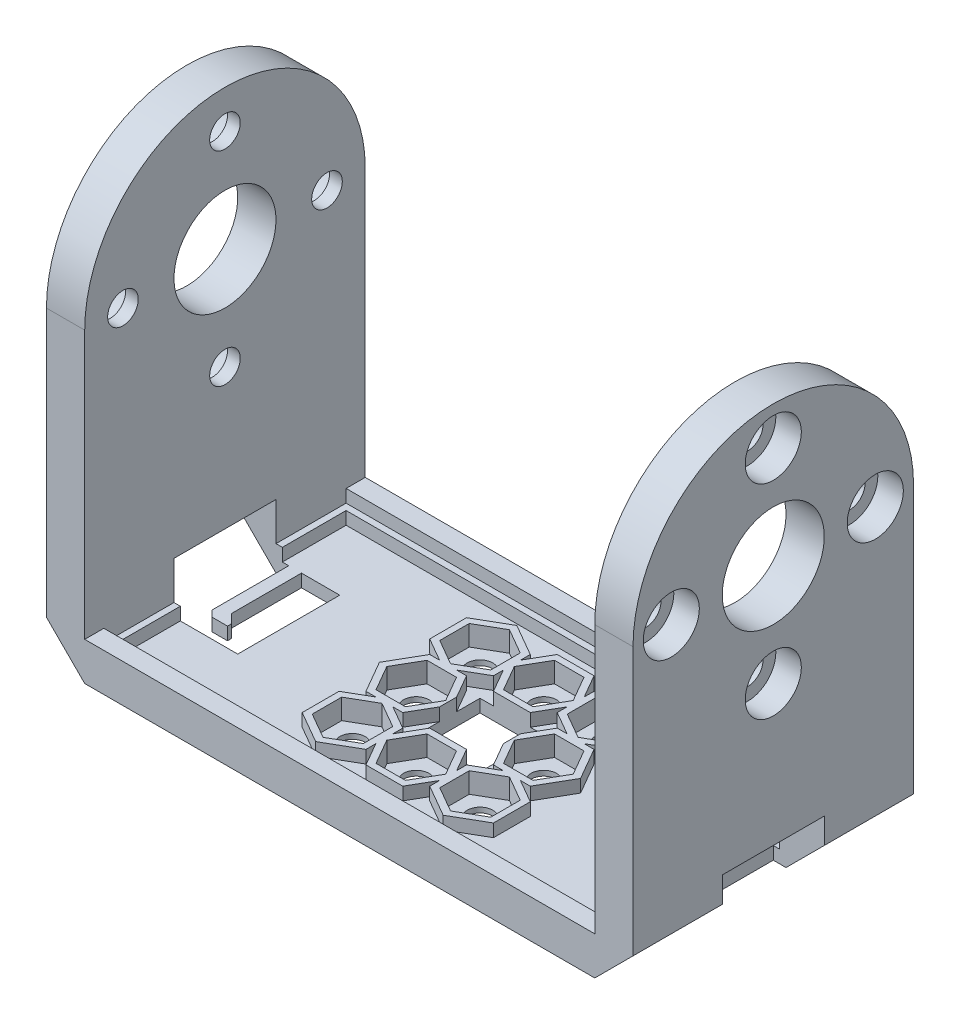
SolidWorks part; units mm, degrees
material "PE High Density"
ref_plane "Front Plane" through (0, 0, 0) normal (0, 0, 1) x (1, 0, 0)
ref_plane "Top Plane" through (0, 0, 0) normal (0, 1, 0) x (1, 0, 0)
ref_plane "Right Plane" through (0, 0, 0) normal (1, 0, 0) x (0, 0, -1)
sketch "Sketch1" plane through (0, 0, 0) normal (0, 1, 0) x (1, 0, 0)
  line L1 (-23, -11) -> (23, -11)
  line L2 (-23, -11) -> (-23, 11)
  line L3 (-23, 11) -> (23, 11)
  line L4 (23, -11) -> (23, 11)
  line L5 (-23, -11) -> (23, 11) construction
  line L6 (-23, 11) -> (23, -11) construction
  point P0 (0, 0)
  dimension "D1" = 22
  dimension "D2" = 46
extrude "Boss-Extrude1" add sketch "Sketch1" along normal blind 3
sketch "Sketch2" plane through (0, 3, 0) normal (0, 1, 0) x (1, 0, 0)
  line L0 (-23, -11) -> (23, -11) construction
  line L1 (-23, 11) -> (-20, 11)
  line L2 (-23, 11) -> (-23, -11)
  line L3 (-23, -11) -> (-20, -11)
  line L4 (-20, 11) -> (-20, -11)
  line L6 (23, 11) -> (20, 11)
  line L7 (23, 11) -> (23, -11)
  line L8 (23, -11) -> (20, -11)
  line L9 (20, 11) -> (20, -11)
  dimension "D1" = 3
  dimension "D2" = 3
extrude "Boss-Extrude2" add sketch "Sketch2" along normal blind 32
sketch "Sketch4" plane through (0, 0, -11) normal (0, 0, -1) x (-1, 0, 0)
  line L0 (-23, 3) -> (-20, 0)
  line L1 (-23, 35) -> (-23, 0) construction
  line L2 (-23, 0) -> (23, 0) construction
  line L3 (23, 3) -> (20, 0)
  line L4 (23, 35) -> (23, 0) construction
  line L5 (23, 3) -> (23, 0)
  line L6 (23, 0) -> (20, 0)
  line L7 (-23, 3) -> (-23, 0)
  line L8 (-23, 0) -> (-20, 0)
  dimension "D1" = 3
  dimension "D2" = 3
  dimension "D3" = 3
  dimension "D4" = 3
extrude "Cut-Extrude2" cut sketch "Sketch4" against normal through all
sketch "Sketch6" plane through (-23, 0, 0) normal (-1, 0, 0) x (0, 0, 1)
  line L0 (-11, 24) -> (11, 24) construction
  line L1 (-11, 35) -> (-11, 3) construction
  line L2 (11, 35) -> (11, 3) construction
  line L3 (-11, 35) -> (11, 35) construction
  line L4 (0, 35) -> (-11, 35)
  line L5 (-11, 35) -> (-11, 24)
  line L6 (0, 35) -> (11, 35)
  line L7 (11, 35) -> (11, 24)
  arc A0 (-11, 24) -> (11, 24) centre (0, 24) cw
  line M1 (-11, 35) -> (-11, 3)
  line M3 (11, 3) -> (11, 35)
  line M4 (11, 35) -> (-11, 35)
  dimension "D1" = 11
extrude "Cut-Extrude3" cut sketch "Sketch6" against normal through all contours A0 M1 M4 | A0 M4 M3
sketch "Sketch7" plane through (-23, 0, 0) normal (-1, 0, 0) x (0, 0, 1)
  circle A0 centre (0, 24) radius 4
  dimension "D1" = 8
extrude "Cut-Extrude4" cut sketch "Sketch7" against normal through all
hole_wizard "CBORE for M2 SHCS1" positions "Sketch10" profile "Sketch11" counterbore size "M2" standard "Ansi Metric"
sketch "Sketch10" plane through (-23, 0, 0) normal (-1, 0, 0) x (0, 0, 1)
  circle A1 centre (0, 24) radius 4 construction
  point P0 (0, 32)
  point P1 (8, 24)
  point P3 (0, 16)
  point P5 (-8, 24)
  dimension "D1" = 8
  dimension "D2" = 8
  dimension "D3" = 8
  dimension "D4" = 8
sketch "Sketch11" plane through (-23, 32, 0) normal (0, 1, 0) x (0, 0, 1)
  line L0 (0, 0) -> (0, 3.721)
  line L1 (0, 3.721) -> (1.2, 3)
  line L2 (1.2, 3) -> (1.2, 2)
  line L3 (1.2, 2) -> (2.2, 2)
  line L4 (2.2, 2) -> (2.2, 0)
  line L5 (2.2, 0) -> (0, 0)
  line L10 (0, 3.721) -> (-1.2, 3) construction
  line L11 (0, -6.35) -> (0, 107.95) construction
  dimension "Hole Dia." = 2.4
  dimension "Hole Depth" = 3
  dimension "C'Bore Dia." = 4.4
  dimension "C'Bore Depth" = 2
  dimension "Drill Angle" = 118
hole_wizard "CBORE for M2 SHCS2" positions "Sketch14" profile "Sketch13" counterbore size "M2" standard "Ansi Metric" end condition through all
sketch "Sketch14" plane through (23, 0, 0) normal (1, 0, 0) x (0, 0, -1)
  point P0 (0, 32)
  point P1 (8, 24)
  point P3 (0, 16)
  point P5 (-8, 24)
sketch "Sketch13" plane through (23, 32, 0) normal (0, 1, 0) x (0, 0, -1)
  line L0 (0, 0) -> (0, 46)
  line L1 (0, 46) -> (1.2, 46)
  line L3 (1.2, 46) -> (1.2, 2)
  line L4 (1.2, 2) -> (2.2, 2)
  line L5 (2.2, 2) -> (2.2, 0)
  line L7 (2.2, 0) -> (0, 0)
  line L11 (0, -6.35) -> (0, 107.95) construction
  dimension "Thru Hole Dia." = 2.4
  dimension "Thru Hole Depth" = 46
  dimension "C'Bore Dia." = 4.4
  dimension "C'Bore Depth" = 2
sketch "Sketch15" plane through (0, 3, 0) normal (0, 1, 0) x (1, 0, 0)
  line L0 (20, 11) -> (20, -11) construction
  line L1 (-20, -9.5) -> (20, -9.5)
  line L2 (-20, -9.5) -> (-20, 9.5)
  line L3 (-20, 9.5) -> (20, 9.5)
  line L4 (20, -9.5) -> (20, 9.5)
  line L5 (-20, -9.5) -> (20, 9.5) construction
  line L6 (-20, 9.5) -> (20, -9.5) construction
  line L7 (20, 11) -> (-20, 11) construction
  point P0 (0, 0)
  dimension "D1" = 1.5
extrude "Cut-Extrude5" cut sketch "Sketch15" against normal blind 1
sketch "Sketch17" plane through (0, 2, 0) normal (0, 1, 0) x (1, 0, 0)
  line L0 (0, 8.0005) -> (0, -20.9995) construction
  line L3 (-17.8458, 0) -> (17.8458, 0) construction
  line L7 (-3, 3.8453) -> (-3, 6.1547)
  line L8 (-3, 6.1547) -> (-5, 7.3094)
  line L9 (-5, 7.3094) -> (-7, 6.1547)
  line L10 (-7, 6.1547) -> (-7, 3.8453)
  line L11 (-7, 3.8453) -> (-5, 2.6906)
  line L12 (-5, 2.6906) -> (-3, 3.8453)
  line L13 (1.1547, 3) -> (2.3094, 5)
  line L14 (2.3094, 5) -> (1.1547, 7)
  line L15 (1.1547, 7) -> (-1.1547, 7)
  line L16 (-1.1547, 7) -> (-2.3094, 5)
  line L17 (-2.3094, 5) -> (-1.1547, 3)
  line L18 (-1.1547, 3) -> (1.1547, 3)
  line L19 (5, 2.6906) -> (7, 3.8453)
  line L20 (7, 3.8453) -> (7, 6.1547)
  line L21 (7, 6.1547) -> (5, 7.3094)
  line L22 (5, 7.3094) -> (3, 6.1547)
  line L23 (3, 6.1547) -> (3, 3.8453)
  line L24 (3, 3.8453) -> (5, 2.6906)
  line L25 (-3.8453, -2) -> (-2.6906, 0)
  line L26 (-2.6906, 0) -> (-3.8453, 2)
  line L27 (-3.8453, 2) -> (-6.1547, 2)
  line L28 (-6.1547, 2) -> (-7.3094, 0)
  line L29 (-7.3094, 0) -> (-6.1547, -2)
  line L30 (-6.1547, -2) -> (-3.8453, -2)
  line L31 (0, -2.3094) -> (2, -1.1547)
  line L32 (2, -1.1547) -> (2, 1.1547)
  line L33 (2, 1.1547) -> (0, 2.3094)
  line L34 (0, 2.3094) -> (-2, 1.1547)
  line L35 (-2, 1.1547) -> (-2, -1.1547)
  line L36 (-2, -1.1547) -> (0, -2.3094)
  line L37 (7.3094, 0) -> (6.1547, 2)
  line L38 (6.1547, 2) -> (3.8453, 2)
  line L39 (3.8453, 2) -> (2.6906, 0)
  line L40 (2.6906, 0) -> (3.8453, -2)
  line L41 (3.8453, -2) -> (6.1547, -2)
  line L42 (6.1547, -2) -> (7.3094, 0)
  line L43 (-3, -6.1547) -> (-3, -3.8453)
  line L44 (-3, -3.8453) -> (-5, -2.6906)
  line L45 (-5, -2.6906) -> (-7, -3.8453)
  line L46 (-7, -3.8453) -> (-7, -6.1547)
  line L47 (-7, -6.1547) -> (-5, -7.3094)
  line L48 (-5, -7.3094) -> (-3, -6.1547)
  line L49 (1.1547, -7) -> (2.3094, -5)
  line L50 (2.3094, -5) -> (1.1547, -3)
  line L51 (1.1547, -3) -> (-1.1547, -3)
  line L52 (-1.1547, -3) -> (-2.3094, -5)
  line L53 (-2.3094, -5) -> (-1.1547, -7)
  line L54 (-1.1547, -7) -> (1.1547, -7)
  line L55 (5, -7.3094) -> (7, -6.1547)
  line L56 (7, -6.1547) -> (7, -3.8453)
  line L57 (7, -3.8453) -> (5, -2.6906)
  line L58 (5, -2.6906) -> (3, -3.8453)
  line L59 (3, -3.8453) -> (3, -6.1547)
  line L60 (3, -6.1547) -> (5, -7.3094)
  circle A0 centre (-5, 5) radius 2 construction
  circle A1 centre (0, 5) radius 2 construction
  circle A2 centre (5, 5) radius 2 construction
  circle A3 centre (-5, 0) radius 2 construction
  circle A4 centre (0, 0) radius 2 construction
  circle A5 centre (5, 0) radius 2 construction
  circle A6 centre (-5, -5) radius 2 construction
  circle A7 centre (0, -5) radius 2 construction
  circle A8 centre (5, -5) radius 2 construction
  dimension "D1" = 4
  dimension "D2" = 4
  dimension "D3" = 4
  dimension "D4" = 4
  dimension "D5" = 4
  dimension "D6" = 4
  dimension "D7" = 4
  dimension "D8" = 4
  dimension "D9" = 4
  dimension "D10" = 5
  dimension "D11" = 5
  dimension "D12" = 5
  dimension "D13" = 5
  dimension "D14" = 5
  dimension "D15" = 5
  dimension "D16" = 5
  dimension "D17" = 5
  dimension "D18" = 5
  dimension "D19" = 5
  dimension "D20" = 5
  dimension "D21" = 5
extrude "Cut-Extrude7" cut sketch "Sketch17" against normal blind 1.6
hole_wizard "Ø2.0 (2) Diameter Hole1" positions "Sketch19" profile "Sketch20" hole size "Ø2.0" standard "Ansi Metric"
sketch "Sketch19" plane through (0, 0.4, 0) normal (0, 1, 0) x (1, 0, 0)
  line L3 (-7.3094, 0) -> (-6.1547, -2) construction
  line L4 (6.1547, -2) -> (7.3094, 0) construction
  line L5 (3.8453, -2) -> (6.1547, -2) construction
  line L6 (-6.1547, -2) -> (-3.8453, -2) construction
  line L7 (-1.1547, 7) -> (-2.3094, 5) construction
  line L8 (2.3094, 5) -> (1.1547, 7) construction
  line L9 (5, 7.3094) -> (3, 6.1547) construction
  line L10 (7, 6.1547) -> (5, 7.3094) construction
  line L11 (-5, 7.3094) -> (-7, 6.1547) construction
  line L12 (-3, 3.8453) -> (-3, 6.1547) construction
  line L13 (-7, -6.1547) -> (-5, -7.3094) construction
  line L14 (-3, -6.1547) -> (-3, -3.8453) construction
  line L15 (-2.3094, -5) -> (-1.1547, -7) construction
  line L16 (1.1547, -7) -> (2.3094, -5) construction
  line L17 (3, -3.8453) -> (3, -6.1547) construction
  line L18 (5, -7.3094) -> (7, -6.1547) construction
  point P0 (5, 0)
  point P1 (0, 5)
  point P3 (5, 5)
  point P5 (0, -5)
  point P7 (0, 0)
  point P10 (-5, 0)
  point P12 (-5, -5)
  point P14 (-5, 5)
  point P16 (5, -5)
  point P72 (6.7321, -1)
  point P75 (5, -2)
  point P78 (-5, -2)
  point P81 (-1.7321, 6)
  point P84 (1.7321, 6)
  point P87 (4, 6.7321)
  point P90 (6, 6.7321)
  point P95 (-3, 5)
  point P104 (1.7321, -6)
  point P107 (3, -5)
  dimension "D1" = 2
  dimension "D2" = 2
  dimension "D3" = 2
  dimension "D4" = 2
  dimension "D5" = 2
  dimension "D6" = 2
  dimension "D7" = 2
  dimension "D8" = 2
  dimension "D9" = 2
  dimension "D10" = 2
  dimension "D11" = 2
  dimension "D12" = 2
  dimension "D13" = 2
  dimension "D14" = 2
  dimension "D15" = 2
  dimension "D16" = 2
sketch "Sketch20" plane through (5, 0.4, 0) normal (1, 0, 0) x (0, 0, 1)
  line L0 (0, 0) -> (0, 10.6009)
  line L1 (0, 10.6009) -> (1, 10)
  line L2 (1, 10) -> (1, 0)
  line L5 (1, 0) -> (0, 0)
  line L10 (0, 10.6009) -> (-1, 10) construction
  line L11 (0, -6.35) -> (0, 107.95) construction
  dimension "Hole Dia." = 2
  dimension "Hole Depth" = 10
  dimension "Drill Angle" = 118
sketch "Sketch21" plane through (0, 2, 0) normal (0, 1, 0) x (1, 0, 0)
  line L1 (-2.5, 2.5) -> (2.5, 2.5)
  line L2 (-2.5, 2.5) -> (-2.5, -2.5)
  line L3 (-2.5, -2.5) -> (2.5, -2.5)
  line L4 (2.5, 2.5) -> (2.5, -2.5)
  line L5 (-2.5, 2.5) -> (2.5, -2.5) construction
  line L6 (-2.5, -2.5) -> (2.5, 2.5) construction
  point P0 (0, 0)
  dimension "D1" = 5
  dimension "D2" = 5
extrude "Cut-Extrude8" cut sketch "Sketch21" against normal through all
sketch "Sketch22" plane through (0, 2, 0) normal (0, 1, 0) x (1, 0, 0)
  line L0 (4.3301, 2.5) -> (3.5566, 2.5)
  line L1 (5.6699, -2.5) -> (6.4434, -2.5)
  line L2 (2.5, -5.6699) -> (2.5, -6.4434)
  line L3 (-2.5, -4.3301) -> (-2.5, -3.5566)
  line L4 (-4.3301, -2.5) -> (-3.5566, -2.5)
  line L5 (-5.6699, 2.5) -> (-6.4434, 2.5)
  line L6 (-1.4434, 2.5) -> (-2.5, 2.5)
  line L7 (-2.5, 2.5) -> (-2.5, 0.6699)
  line L8 (-2.5, -2.5) -> (-1.4434, -2.5)
  line L9 (1.4434, -2.5) -> (2.5, -2.5)
  line L10 (2.5, -2.5) -> (2.5, -0.6699)
  line L11 (2.5, 2.5) -> (1.4434, 2.5)
  line L12 (2.5, 0.6699) -> (2.5, 2.5)
  line L13 (-2.5, -0.6699) -> (-2.5, -2.5)
  line L27 (-7.5, 6.4434) -> (-7.5, 3.5566)
  line L28 (-7.5, 3.5566) -> (-5, 2.1132)
  line L29 (-5, 2.1132) -> (-2.5, 3.5566)
  line L30 (-2.5, 3.5566) -> (-2.5, 6.4434)
  line L31 (-2.5, 6.4434) -> (-5, 7.8868)
  line L32 (-5, 7.8868) -> (-7.5, 6.4434)
  line L33 (-7.5, 6.4434) -> (-7.5, 3.5566)
  line L34 (-7.5, 3.5566) -> (-5.6699, 2.5)
  line L35 (-4.3301, 2.5) -> (-2.5, 3.5566)
  line L36 (-2.5, 3.5566) -> (-2.5, 4.3301)
  line L37 (-2.5, 6.4434) -> (-5, 7.8868)
  line L38 (-5, 7.8868) -> (-7.5, 6.4434)
  line L60 (2.8868, 5) -> (1.4434, 7.5)
  line L61 (1.4434, 2.5) -> (2.8868, 5)
  line L62 (-1.4434, 2.5) -> (1.4434, 2.5)
  line L63 (-2.8868, 5) -> (-1.4434, 2.5)
  line L64 (-1.4434, 7.5) -> (-2.8868, 5)
  line L65 (1.4434, 7.5) -> (-1.4434, 7.5)
  line L66 (2.5, 5.6699) -> (1.4434, 7.5)
  line L67 (1.4434, 2.5) -> (2.5, 4.3301)
  line L69 (-2.5, 4.3301) -> (-1.4434, 2.5)
  line L70 (-1.4434, 7.5) -> (-2.5, 5.6699)
  line L71 (1.4434, 7.5) -> (-1.4434, 7.5)
  line L93 (2.5, 6.4434) -> (2.5, 3.5566)
  line L94 (2.5, 3.5566) -> (5, 2.1132)
  line L95 (5, 2.1132) -> (7.5, 3.5566)
  line L96 (7.5, 3.5566) -> (7.5, 6.4434)
  line L97 (7.5, 6.4434) -> (5, 7.8868)
  line L98 (5, 7.8868) -> (2.5, 6.4434)
  line L99 (2.5, 6.4434) -> (2.5, 5.6699)
  line L100 (2.5, 3.5566) -> (4.3301, 2.5)
  line L101 (5.6699, 2.5) -> (7.5, 3.5566)
  line L102 (7.5, 3.5566) -> (7.5, 6.4434)
  line L103 (7.5, 6.4434) -> (5, 7.8868)
  line L104 (5, 7.8868) -> (2.5, 6.4434)
  line L126 (-2.1132, 0) -> (-3.5566, 2.5)
  line L127 (-3.5566, -2.5) -> (-2.1132, 0)
  line L128 (-6.4434, -2.5) -> (-3.5566, -2.5)
  line L129 (-7.8868, 0) -> (-6.4434, -2.5)
  line L130 (-6.4434, 2.5) -> (-7.8868, 0)
  line L131 (-3.5566, 2.5) -> (-6.4434, 2.5)
  line L132 (-2.5, 0.6699) -> (-3.5566, 2.5)
  line L133 (-3.5566, -2.5) -> (-2.5, -0.6699)
  line L134 (-6.4434, -2.5) -> (-5.6699, -2.5)
  line L135 (-7.8868, 0) -> (-6.4434, -2.5)
  line L136 (-6.4434, 2.5) -> (-7.8868, 0)
  line L137 (-3.5566, 2.5) -> (-4.3301, 2.5)
  line L159 (2.1132, 0) -> (3.5566, -2.5)
  line L160 (3.5566, -2.5) -> (6.4434, -2.5)
  line L161 (6.4434, -2.5) -> (7.8868, 0)
  line L162 (7.8868, 0) -> (6.4434, 2.5)
  line L163 (6.4434, 2.5) -> (3.5566, 2.5)
  line L164 (3.5566, 2.5) -> (2.1132, 0)
  line L165 (2.5, -0.6699) -> (3.5566, -2.5)
  line L166 (3.5566, -2.5) -> (4.3301, -2.5)
  line L167 (6.4434, -2.5) -> (7.8868, 0)
  line L168 (7.8868, 0) -> (6.4434, 2.5)
  line L169 (6.4434, 2.5) -> (5.6699, 2.5)
  line L170 (3.5566, 2.5) -> (2.5, 0.6699)
  line L192 (-2.5, -6.4434) -> (-2.5, -3.5566)
  line L193 (-5, -7.8868) -> (-2.5, -6.4434)
  line L194 (-7.5, -6.4434) -> (-5, -7.8868)
  line L195 (-7.5, -3.5566) -> (-7.5, -6.4434)
  line L196 (-5, -2.1132) -> (-7.5, -3.5566)
  line L197 (-2.5, -3.5566) -> (-5, -2.1132)
  line L198 (-2.5, -6.4434) -> (-2.5, -5.6699)
  line L199 (-5, -7.8868) -> (-2.5, -6.4434)
  line L200 (-7.5, -6.4434) -> (-5, -7.8868)
  line L201 (-7.5, -3.5566) -> (-7.5, -6.4434)
  line L202 (-5.6699, -2.5) -> (-7.5, -3.5566)
  line L203 (-2.5, -3.5566) -> (-4.3301, -2.5)
  line L225 (2.8868, -5) -> (1.4434, -2.5)
  line L226 (1.4434, -7.5) -> (2.8868, -5)
  line L227 (-1.4434, -7.5) -> (1.4434, -7.5)
  line L228 (-2.8868, -5) -> (-1.4434, -7.5)
  line L229 (-1.4434, -2.5) -> (-2.8868, -5)
  line L230 (1.4434, -2.5) -> (-1.4434, -2.5)
  line L231 (2.5, -4.3301) -> (1.4434, -2.5)
  line L232 (1.4434, -7.5) -> (2.5, -5.6699)
  line L233 (-1.4434, -7.5) -> (1.4434, -7.5)
  line L234 (-2.5, -5.6699) -> (-1.4434, -7.5)
  line L235 (-1.4434, -2.5) -> (-2.5, -4.3301)
  line L258 (7.5, -6.4434) -> (7.5, -3.5566)
  line L259 (5, -7.8868) -> (7.5, -6.4434)
  line L260 (2.5, -6.4434) -> (5, -7.8868)
  line L261 (2.5, -3.5566) -> (2.5, -6.4434)
  line L262 (5, -2.1132) -> (2.5, -3.5566)
  line L263 (7.5, -3.5566) -> (5, -2.1132)
  line L264 (7.5, -6.4434) -> (7.5, -3.5566)
  line L265 (5, -7.8868) -> (7.5, -6.4434)
  line L266 (2.5, -6.4434) -> (5, -7.8868)
  line L267 (2.5, -3.5566) -> (2.5, -4.3301)
  line L268 (4.3301, -2.5) -> (2.5, -3.5566)
  line L269 (7.5, -3.5566) -> (5.6699, -2.5)
  line L277 (-2.5, 5.6699) -> (-2.5, 6.4434)
  line L278 (2.5, 4.3301) -> (2.5, 3.5566)
  line L281 (19.5, -9) -> (19.5, 9)
  line L282 (-19.5, -9) -> (19.5, -9)
  line L283 (-19.5, 9) -> (-19.5, -9)
  line L284 (19.5, 9) -> (-19.5, 9)
  line L285 (19.5, -9) -> (19.5, 9)
  line L286 (-19.5, -9) -> (19.5, -9)
  line L287 (-19.5, 9) -> (-19.5, -9)
  line L288 (19.5, 9) -> (-19.5, 9)
  dimension "D1" = 0.5
  dimension "D2" = 0.5
  dimension "D3" = 0.5
  dimension "D4" = 0.5
  dimension "D5" = 0.5
  dimension "D6" = 0.5
  dimension "D7" = 0.5
  dimension "D8" = 0.5
  dimension "D9" = 0.5
extrude "Cut-Extrude9" cut sketch "Sketch22" against normal blind 1 contours L285 L288 L287 L286 L277 L70 L71 L66 L99 L104 L103 L102 L101 L169 L168 L167 L1 L269 L264 L265 L266 L2 L232 L233 L234 L198 L199 L200 L201 L202 L134 L135 L136 L5 L34 L33 L38 L37 | L137 L132 L7 L6 L69 L36 L35 | L278 L67 L11 L12 L170 L0 L100 | L268 L166 L165 L10 L9 L231 L267 | L235 L8 L13 L133 L4 L203 L3
sketch "Sketch23" plane through (-23, 0, 0) normal (-1, 0, 0) x (0, 0, 1)
  line L0 (11, 3) -> (-11, 3) construction
  line L1 (-4, 5) -> (4, 5)
  line L2 (-4, 5) -> (-4, 1)
  line L3 (-4, 1) -> (4, 1)
  line L4 (4, 5) -> (4, 1)
  line L5 (-4, 5) -> (4, 1) construction
  line L6 (-4, 1) -> (4, 5) construction
  line L7 (-9, 1) -> (9, 1) construction
  point P0 (0, 3)
  dimension "D1" = 8
extrude "Cut-Extrude10" cut sketch "Sketch23" against normal blind 11
sketch "Sketch24" plane through (0, 0, 0) normal (0, -1, 0) x (1, 0, 0)
  line L1 (-21, 4) -> (-15, 4)
  line L2 (-21, 4) -> (-21, -4)
  line L3 (-21, -4) -> (-15, -4)
  line L4 (-15, 4) -> (-15, -4)
  line L5 (21, 4) -> (15, 4)
  line L6 (21, 4) -> (21, -4)
  line L7 (21, -4) -> (15, -4)
  line L8 (15, 4) -> (15, -4)
  dimension "D1" = 8
  dimension "D2" = 6
  dimension "D3" = 6
extrude "Cut-Extrude11" cut sketch "Sketch24" against normal blind 3
sketch "Sketch25" plane through (0, 0, 0) normal (0, -1, 0) x (1, 0, 0)
  line L0 (-19, -4) -> (-19, 2)
  line L1 (-20, -4) -> (-15, -4) construction
  line L2 (-19, 2) -> (-18.5, 2.5)
  line L3 (-18.5, 2.5) -> (-17.3, 2.5)
  line L4 (-17.3, 2.5) -> (-17.3, 2.2)
  line L5 (-17.3, 2.2) -> (-18, 1.5)
  line L6 (-18, 1.5) -> (-18, -4)
  line L8 (19, -4) -> (19, 2)
  line L9 (-20, -4) -> (-15, -4) construction
  line L11 (18, -4) -> (18, 1.5)
  line L12 (19, 2) -> (18.5, 2.5)
  line L13 (18.5, 2.5) -> (17.3, 2.5)
  line L14 (17.3, 2.5) -> (17.3, 2.2)
  line L15 (17.3, 2.2) -> (18, 1.5)
  line L16 (18, -4) -> (19, -4)
  line L17 (-19, -4) -> (-18, -4)
  line L18 (15, -4) -> (20, -4) construction
  point P4 (-17.5, -4)
  point P22 (17.5, -4)
  dimension "D1" = 6
  dimension "D2" = 5.5
  dimension "D3" = 0.5
  dimension "D4" = 1.2
  dimension "D5" = 1
  dimension "D6" = 0.5
  dimension "D7" = 0.3
  dimension "D8" = 6
  dimension "D9" = 5.5
  dimension "D10" = 1
  dimension "D11" = 0.5
  dimension "D12" = 0.5
  dimension "D13" = 45
  dimension "D14" = 1.2
  dimension "D15" = 0.3
sketch "Sketch26" plane through (23, 0, 0) normal (1, 0, 0) x (0, 0, -1)
  line L0 (-11, 3) -> (11, 3) construction
  line L1 (-4, 1) -> (4, 1)
  line L2 (-4, 1) -> (-4, 5)
  line L3 (-4, 5) -> (4, 5)
  line L4 (4, 1) -> (4, 5)
  line L5 (-4, 1) -> (4, 5) construction
  line L6 (-4, 5) -> (4, 1) construction
  point P0 (0, 3)
extrude "Cut-Extrude12" cut sketch "Sketch26" against normal blind 11
extrude "Boss-Extrude4" add sketch "Sketch25" against normal blind 1
